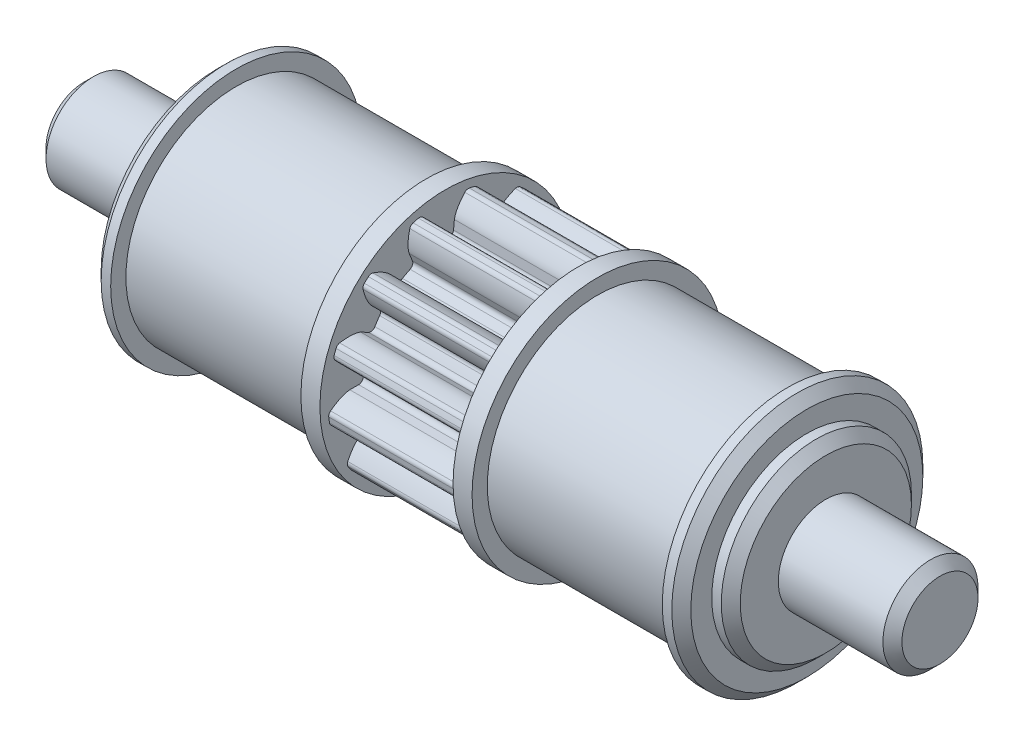
SolidWorks part; units mm, degrees
ref_plane "Front Plane" through (0, 0, 0) normal (0, 0, 1) x (1, 0, 0)
ref_plane "Top Plane" through (0, 0, 0) normal (0, 1, 0) x (1, 0, 0)
ref_plane "Right Plane" through (0, 0, 0) normal (1, 0, 0) x (0, 0, -1)
sketch "Sketch2" plane through (0, 0, 0) normal (1, 0, 0) x (0, -1, 0)
  circle A0 centre (0, 0) radius 6.1731
  dimension "D1" = 12.3462
extrude "Boss-Extrude1" add sketch "Sketch2" along normal mid plane 7
sketch "Sketch3" plane through (3.5, 0, 0) normal (1, 0, 0) x (0, 0, -1)
  line L0 (0, 0) -> (-5.0274, 0) construction
  line L1 (0, 0) -> (-5.3495, -0.0724) construction
  line L2 (0, 0) -> (-6.1376, 0.6611) construction
  line L3 (4.3212, 0) -> (-5.0274, 0)
  line L4 (-4.2963, 0.4628) -> (-6.1376, 0.6611)
  circle A0 centre (0, 0) radius 5.35
  circle A1 centre (0, 0) radius 5.0274
  circle A2 centre (0, 0) radius 4.3212
  circle A3 centre (0, 0) radius 6.1731 construction
  arc A4 (-5.0274, 0) -> (-4.9984, 0.5384) centre (0, 0) cw
  arc A5 (-6.1376, 0.6611) -> (-6.149, -0.5448) centre (0, 0) ccw
  spline S0 degree 4 poles (-5.0274, 0) (-5.0311, 0) (-5.0415, -0.0002) (-5.0612, -0.0017) (-5.0932, -0.0053) (-5.1338, -0.012) (-5.1859, -0.023) (-5.2468, -0.0387) (-5.313, -0.0591) (-5.3843, -0.0845) (-5.4545, -0.1126) (-5.5237, -0.1433) (-5.5918, -0.1762) (-5.6733, -0.2187) (-5.7694, -0.2735) (-5.8793, -0.3428) (-6.0009, -0.4277) (-6.1212, -0.5205) (-6.2365, -0.6172) (-6.3492, -0.7205) (-6.4555, -0.8246) (-6.5617, -0.9384) (-6.6576, -1.0463) (-6.7601, -1.173) (-6.8414, -1.2771) (-6.943, -1.4204) (-7.0014, -1.5067) (-7.0677, -1.6098) (-7.0961, -1.6566) (-7.1136, -1.6854) knots 0 0 0 0 0 0.005377 0.015084 0.028532 0.04661 0.064855 0.092111 0.119476 0.146842 0.174209 0.201575 0.228941 0.256307 0.307035 0.361767 0.4165 0.471232 0.525964 0.580697 0.635429 0.690161 0.744894 0.799626 0.854358 0.909091 0.954545 1 1 1 1 1 construction
  spline S1 degree 4 poles (-5.0274, 0) (-5.0311, 0) (-5.0415, -0.0002) (-5.0612, -0.0017) (-5.0932, -0.0053) (-5.1338, -0.012) (-5.1859, -0.023) (-5.2468, -0.0387) (-5.313, -0.0591) (-5.3843, -0.0845) (-5.4545, -0.1126) (-5.5237, -0.1433) (-5.5918, -0.1762) (-5.6733, -0.2187) (-5.7694, -0.2735) (-5.8793, -0.3428) (-6.0009, -0.4277) (-6.1212, -0.5205) (-6.2365, -0.6172) (-6.3492, -0.7205) (-6.4555, -0.8246) (-6.5617, -0.9384) (-6.6576, -1.0463) (-6.7601, -1.173) (-6.8414, -1.2771) (-6.921, -1.3893) (-6.9591, -1.4446) (-6.9783, -1.4731) knots 0 0 0 0 0 0.005377 0.015084 0.028532 0.04661 0.064855 0.092111 0.119476 0.146842 0.174209 0.201575 0.228941 0.256307 0.307035 0.361767 0.4165 0.471232 0.525964 0.580697 0.635429 0.690161 0.744894 0.799626 0.854358 0.909091 0.909091 0.909091 0.909091 0.909091
  circle M1 centre (0, 0) radius 6.1731
  dimension "D1" = 10.7
  dimension "D2" = 10.0547
  dimension "D3" = 8.6423
  dimension "D4" = 6.923
extrude "Cut-Extrude1" cut sketch "Sketch3" against normal through all contours S1 A0 L4 M1 | S1 A1 L4 A0 | A2 L4 A1 L3
ref_plane "Plane1" through (0, 0, 0) normal (0, 0.9942, -0.1071) x (1, 0, 0)
mirror "Mirror2" about plane through (0, 0, 0) normal (0, 0.9942, -0.1071) of "Cut-Extrude1"
pattern_circular "CirPattern9" count 13 over 360 about axis through (3.5, 0, 0) along (1, 0, 0) of "Mirror2", "Cut-Extrude1"
fillet "Fillet2" radius 0.25 52 edges at (0, -3.6698, -4.9638) (0, -3.1983, -5.2799) (0, -1.9039, -3.8791) (0, -1.0341, -4.1956) (0, -0.9426, -6.1007) (0, -0.3782, -6.1615) (0, 0.1169, -4.3196) (0, 1.0341, -4.1956) (0, 2.0005, -5.8399) (0, 2.5285, -5.6315) (0, 2.1109, -3.7705) (0, 2.8655, -3.2344) (0, 4.4853, -4.2413) (0, 4.8559, -3.8114) (0, 3.6213, -2.3576) (0, 4.0403, -1.5323) (0, 5.9426, -1.6711) (0, 6.071, -1.1182) (0, 4.3022, -0.4046) (0, 4.2896, 0.5209) (0, 6.0385, 1.282) (0, 5.8952, 1.8312) (0, 3.9974, 1.641) (0, 3.5562, 2.4547) (0, 4.7511, 3.9414) (0, 4.3689, 4.3611) (0, 2.7769, 3.3108) (0, 2.0081, 3.8262) (0, 2.3752, 5.6978) (0, 1.8418, 5.8919) (0, 0.9202, 4.222) (0, 0, 4.3212) (0, -0.5448, 6.149) (0, -1.1073, 6.073) (0, -2.0081, 3.8262) (0, -3.3399, 5.1915) (0, -3.8027, 4.8627) (0, -2.9519, 3.1557) (0, -3.5562, 2.4547) (0, -5.37, 3.0447) (0, -5.627, 2.5385) (0, -4.0803, 1.4224) (0, -4.2896, 0.5209) (0, -6.1698, 0.2004) (0, -6.1621, -0.3672) (0, -4.274, -0.6367) (0, -4.0403, -1.5323) (0, -5.5562, -2.6898) (0, -5.2857, -3.1888) (0, -3.4885, -2.55) (0, -2.8655, -3.2344) (0, -1.1472, 4.1661)
sketch "Sketch4" plane through (0, 0, 0) normal (0, 0, 1) x (1, 0, 0)
  line L0 (-5.5703, 0) -> (-9.3794, 0) construction
  line L1 (0, 7.44) -> (0, 11.2901) construction
  line L2 (3.5, 0) -> (3.5, 6.6)
  line L3 (3.5, 6.6) -> (4.5, 6.6)
  line L4 (4.5, 6.6) -> (4.5, 5.8)
  line L5 (4.5, 5.8) -> (14.5, 5.8)
  line L6 (14.5, 5.8) -> (14.5, 6.6)
  line L7 (14.5, 6.6) -> (15.5, 6.6)
  line L8 (15.5, 6.6) -> (15.5, 5)
  line L9 (15.5, 5) -> (16.5, 5)
  line L10 (16.5, 5) -> (16.5, 2.5)
  line L11 (16.5, 2.5) -> (22.5, 2.5)
  line L12 (22.5, 2.5) -> (22.5, 0)
  line L14 (22.5, 0) -> (3.5, 0)
  line L15 (-22.5, 0) -> (-3.5, 0)
  line L16 (-22.5, 2.5) -> (-22.5, 0)
  line L17 (-16.5, 2.5) -> (-22.5, 2.5)
  line L18 (-16.5, 5) -> (-16.5, 2.5)
  line L19 (-15.5, 5) -> (-16.5, 5)
  line L20 (-15.5, 6.6) -> (-15.5, 5)
  line L21 (-14.5, 6.6) -> (-15.5, 6.6)
  line L22 (-14.5, 5.8) -> (-14.5, 6.6)
  line L23 (-4.5, 5.8) -> (-14.5, 5.8)
  line L24 (-4.5, 6.6) -> (-4.5, 5.8)
  line L25 (-3.5, 6.6) -> (-4.5, 6.6)
  line L26 (-3.5, 0) -> (-3.5, 6.6)
  line L27 (3.5, -3.6617) -> (3.5, -3.3338) construction
  dimension "D1" = 1
  dimension "D2" = 10
  dimension "D3" = 45
  dimension "D4" = 6
  dimension "D5" = 11.6
  dimension "D6" = 13.2
  dimension "D7" = 10
  dimension "D8" = 5
revolve "Revolve1" add sketch "Sketch4" angle 360 about L0
chamfer "Chamfer1" distance 0.5 angle 45 6 edges at (22.5, 0, -2.5) (16.5, 0, -5) (15.5, 0, -6.6) (-22.5, 0, -2.5) (-16.5, 0, -5) (-15.5, 0, -6.6)
equation "\"d\"= 10.7'Pitch Circle Diameter"
equation "\"t\"= 13'Number of Teeth"
equation "\"phi\"= 20deg'Pressure Angle"
equation "\"m\"= \"d\" / \"t\"'Module"
equation "\"a\"= \"m\"'Addendum"
equation "\"b\"= 1.25 * \"m\"'Dedendum"
equation "\"c\"= \"b\" - \"a\"'Clearence"
equation "\"db\"= \"d\" * cos ( \"phi\" )'Base Circle Diameter"
equation "\"D1@Sketch2\"=\"d\"+2*\"a\""
equation "\"D1@Sketch3\"=\"d\""
equation "\"D2@Sketch3\"=\"db\""
equation "\"D3@Sketch3\"=\"d\"-2*\"b\""
equation "\"D4@Sketch3\"=360/(4*\"t\")"
equation "\"D1@CirPattern9\"=\"t\""
equation "\"D1@Fillet2\"=0.25"
